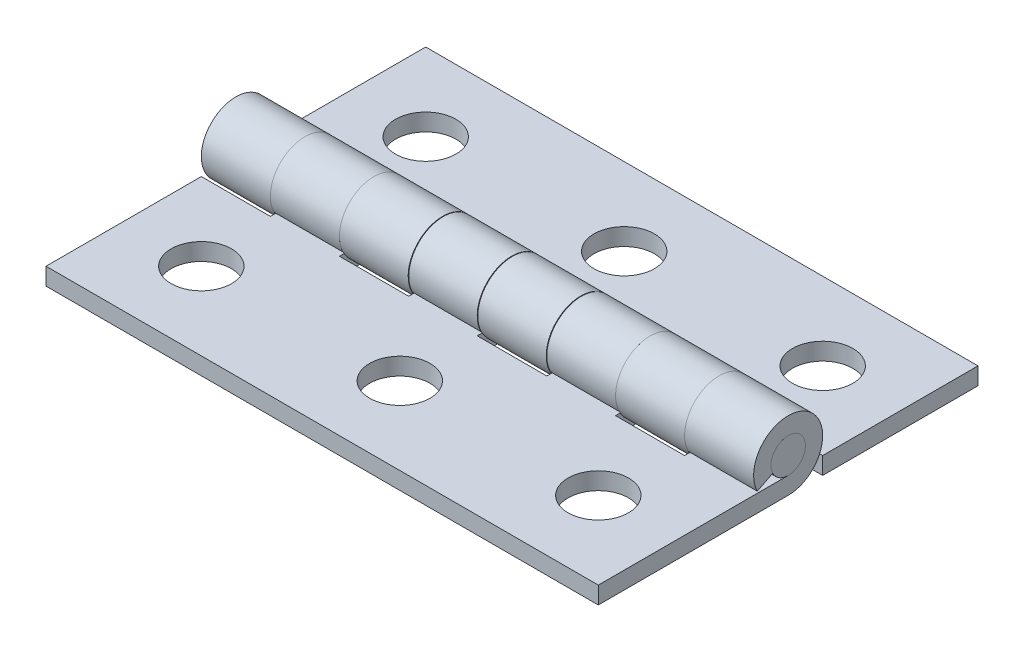
SolidWorks part; units mm, degrees
ref_plane "Front Plane" through (0, 0, 0) normal (0, 0, 1) x (1, 0, 0)
ref_plane "Top Plane" through (0, 0, 0) normal (0, 1, 0) x (1, 0, 0)
ref_plane "Right Plane" through (0, 0, 0) normal (1, 0, 0) x (0, 0, -1)
sketch "Sketch1" plane through (0, 0, 0) normal (0, 1, 0) x (1, 0, 0)
  line L0 (-25.4, 0) -> (25.4, 0) construction
  line L1 (-25.4, -17.4625) -> (-25.4, 17.4625) construction
  line L2 (18.2562, 10.3187) -> (18.2562, -10.3187) construction
  line L3 (-18.2562, -17.4625) -> (18.2562, -17.4625) construction
  line L4 (0, 0) -> (0, -17.4625) construction
  line L5 (18.2562, -7.5406) -> (18.2562, -13.0969) construction
  line L7 (-18.2563, 10.3187) -> (18.2562, 10.3187) construction
  line L8 (-18.2563, 10.3187) -> (-18.2563, -10.3187) construction
  line L9 (-18.2563, -10.3187) -> (18.2562, -10.3187) construction
  line L10 (18.2562, 10.3187) -> (18.2562, -10.3187) construction
  line L11 (21.0344, -10.3187) -> (15.4781, -10.3187) construction
  line L12 (-18.2563, 10.3187) -> (18.2562, -10.3187) construction
  line L13 (-18.2563, -10.3187) -> (18.2562, 10.3187) construction
  circle A0 centre (18.2562, -10.3187) radius 3.9624 construction
  point P4 (0, 0)
  point P8 (-25.4, 0)
  point P17 (-19.05, 0)
  point P21 (18.2562, -10.3187)
  point P25 (18.2562, 0)
  point P26 (18.2562, -10.3187)
  point P38 (18.2562, -10.3187)
  dimension "Screw Head Diameter" = 7.9248
  dimension "Door Leaf Height" = 50.8
  dimension "Overall Width" = 34.925
  dimension "Hole Spacing" = 36.5125
  dimension "Knuckle Length" = 6.35
  dimension "Hole Diameter" = 5.5562
  dimension "Hole Spacing 2" = 20.6375
  dimension "Frame Leaf Height" = 50.8
  dimension "Door Leaf Width" = 17.4625
  dimension "Frame Leaf Width" = 17.4625
sketch "Sketch2" plane through (0, 0, 0) normal (1, 0, 0) x (0, 0, -1)
  line L2 (0, -3.175) -> (0, -1.5875) construction
  line L4 (0, 1.5875) -> (0, -1.5875) construction
  point P8 (0, 0)
  dimension "Leaf Thickness" = 1.5875
  dimension "Pin Diameter" = 3.175
sketch "Sketch3" plane through (0, 0, 0) normal (1, 0, 0) x (0, 0, -1)
  line L3 (0, 0) -> (-3.175, -1.5875) construction
  line L4 (0, -3.175) -> (-17.4625, -3.175)
  line L5 (-17.4625, -3.175) -> (-17.4625, -1.5875)
  line L7 (-17.4625, -1.5875) -> (0, -1.5875)
  line L8 (-17.4625, 0) -> (17.4625, 0) construction
  line L9 (-1.4199, -0.71) -> (-2.8398, -1.4199)
  line L11 (-3.175, 0) -> (-3.175, -1.5875) construction
  circle A4 centre (0, 0) radius 1.5875 construction
  circle A5 centre (0, 0) radius 3.175 construction
  arc A8 (-1.4199, -0.71) -> (0, -1.5875) centre (0, 0) cw
  arc A9 (-2.8398, -1.4199) -> (0, -3.175) centre (0, 0) cw
  point P0 (-2.8398, -1.4199)
  point P13 (-1.4199, -0.71)
extrude "Boss-Extrude1" add sketch "Sketch3" along normal mid plane 50.8
sketch "Sketch4" plane through (0, 0, 0) normal (0, 1, 0) x (1, 0, 0)
  line L0 (-25.4, -3.175) -> (25.4, -3.175) construction
  line L1 (-25.4, -3.175) -> (25.4, -3.175) construction
  line L2 (25.4, 3.175) -> (-25.4, 3.175) construction
  line L3 (25.4, 3.175) -> (-25.4, 3.175) construction
  line L4 (0, -3.175) -> (0, 3.175)
  line L6 (0, 3.175) -> (6.35, 3.175)
  line L7 (6.35, -3.175) -> (0, -3.175)
  line L8 (6.35, 3.175) -> (6.35, -3.175)
  point P8 (-19.05, 0)
  dimension "D1" = 6.35
extrude "Cut-Extrude1" cut sketch "Sketch4" against normal through all both and the other way through all
pattern_linear "LPattern1" count 3 spacing 12.7 along (-1, 0, 0) count 2 spacing 12.7 along (1, 0, 0) of "Cut-Extrude1"
sketch "Sketch5" plane through (0, -1.5875, 0) normal (0, 1, 0) x (1, 0, 0)
  line L0 (-6.35, -3.175) -> (0, -3.175) construction
  line L1 (-6.35, 3.175) -> (-6.3246, 3.175)
  line L2 (-6.35, 3.175) -> (-6.35, -3.175)
  line L3 (-6.35, -3.175) -> (-6.3246, -3.175)
  line L4 (-6.3246, 3.175) -> (-6.3246, -3.175)
  line L5 (6.35, 3.175) -> (6.35, -3.175) construction
  line L6 (0, 3.175) -> (-0.0254, 3.175)
  line L7 (0, 3.175) -> (0, -3.175)
  line L8 (0, -3.175) -> (-0.0254, -3.175)
  line L9 (-0.0254, 3.175) -> (-0.0254, -3.175)
  line L10 (6.35, 3.175) -> (6.3754, 3.175)
  line L11 (6.35, 3.175) -> (6.35, -3.175)
  line L12 (6.35, -3.175) -> (6.3754, -3.175)
  line L13 (6.3754, 3.175) -> (6.3754, -3.175)
  line L14 (19.05, -3.175) -> (25.4, -3.175) construction
  line L15 (25.4, 3.175) -> (19.05, 3.175) construction
  dimension "D1" = 0.0254
extrude "Cut-Extrude2" cut sketch "Sketch5" against normal through all both and the other way through all
sketch "Sketch6" plane through (0, -1.5875, 0) normal (0, 1, 0) x (1, 0, 0)
  line L0 (18.2562, -10.3187) -> (-18.2563, -10.3188) construction
  line L1 (18.2562, -10.3187) -> (18.2562, -17.4625) construction
  line L2 (-18.2563, -10.3188) -> (-18.2562, -17.4625) construction
  line L3 (18.2562, -10.3187) -> (19.6453, -12.7247) construction
  circle A0 centre (18.2562, -10.3187) radius 2.7781
  circle A3 centre (-18.2563, -10.3188) radius 2.7781
  circle A4 centre (0, -10.3188) radius 2.7781
  point P7 (19.6453, -12.7247)
  dimension "D1" = 30
extrude "Cut-Extrude3" cut sketch "Sketch6" against normal through all
sketch "Sketch7" plane through (0, -1.5875, 0) normal (0, 1, 0) x (1, 0, 0)
  circle A0 centre (-18.2563, -10.3188) radius 3.9624
  circle A1 centre (18.2562, -10.3187) radius 3.9624
  circle A2 centre (18.2562, -10.3187) radius 3.9624 construction
extrude "Cut-Extrude4" [suppressed] cut sketch "Sketch7" against normal through all draft 41
fillet "Fillet1" [suppressed] radius 1.5875
pattern_circular "CirPattern1" count 2 over 360 about axis through (0, 0, 0) along (0, 1, 0) of bodies 107
sketch "Sketch8" plane through (0, 0, 0) normal (1, 0, 0) x (0, 0, -1)
  circle A0 centre (0, 0) radius 1.5875
  dimension "D1" = 3.175
extrude "Boss-Extrude2" add sketch "Sketch8" along normal mid plane 50.8 separate body
sketch "Sketch9" plane through (0, 0, 0) normal (0, 0, 1) x (1, 0, 0)
  line L0 (-25.4, 0) -> (25.4, 0) construction
  line L2 (25.4, 2.3813) -> (25.4, -2.3813) construction
  line L3 (25.4, 0) -> (26.1937, 0) construction
  line L7 (25.4, 2.3813) -> (25.4, 0)
  line L8 (25.4, 0) -> (26.1937, 0)
  line L9 (25.4, -1.5875) -> (25.4, -3.175) construction
  line L10 (-25.4, -2.3813) -> (25.4, -2.3813) construction
  line L12 (25.4, 2.3813) -> (25.613, 2.3813)
  line L13 (25.4, 1.5875) -> (25.4, 3.175) construction
  line L15 (0, -2.3813) -> (0, 3.175) construction
  line L17 (-25.4, 0) -> (-26.1937, 0) construction
  line L18 (-25.4, 2.3813) -> (-25.613, 2.3813)
  line L19 (-25.4, 0) -> (-26.1937, 0)
  line L20 (-25.4, 2.3813) -> (-25.4, 0)
  line L21 (25.4, 1.5875) -> (19.05, 1.5875) construction
  line L22 (25.4, 3.175) -> (19.05, 3.175) construction
  line L23 (6.3246, 3.175) -> (0.0254, 3.175) construction
  arc A0 (25.4, 2.3813) -> (25.4, -2.3813) centre (22.225, 0) cw construction
  arc A4 (25.8553, 2.2035) -> (26.1937, 0) centre (18.8516, 0) cw
  arc A5 (25.613, 2.3813) -> (25.8553, 2.2035) centre (25.613, 2.1273) cw
  arc A6 (-25.613, 2.3813) -> (-25.8553, 2.2035) centre (-25.613, 2.1273) ccw
  arc A7 (-25.8553, 2.2035) -> (-26.1937, 0) centre (-18.8516, 0) ccw
  point P12 (25.4, 0)
  point P20 (25.7969, 0)
  point P29 (25.7969, 2.3813)
  point P34 (-25.7969, 2.3813)
  point P35 (-25.7969, 0)
  point P36 (25.4, 2.3813)
  dimension "D2" = 0.254
  dimension "D1" = 0.7937
revolve "Revolve1" [suppressed] add sketch "Sketch9" angle 360 about L0
equation "\"D1@Boss-Extrude1\" = \"Door Leaf Height@Sketch1\""
equation "\"D1@Sketch4\"=\"Knuckle Length@Sketch1\""
equation "\"D3@LPattern1\"=\"Knuckle Length@Sketch1\"*2"
equation "\"D1@Sketch8\" = \"Pin Diameter@Sketch2\""
equation "\"D1@Boss-Extrude2\" = \"Door Leaf Height@Sketch1\""
equation "\"D4@LPattern1\"=\"Knuckle Length@Sketch1\"*2"
